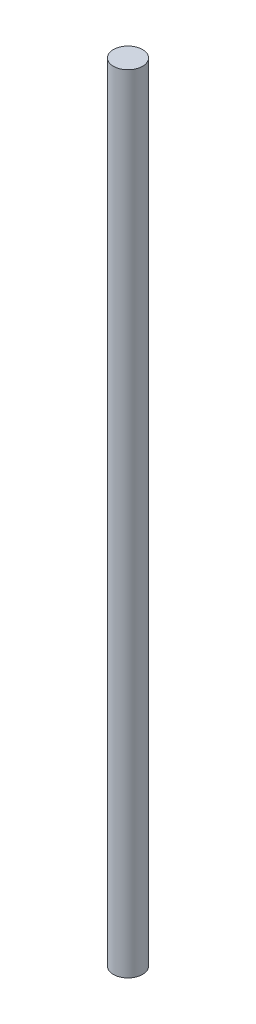
SolidWorks part; units mm, degrees
ref_plane "Front Plane" through (0, 0, 0) normal (0, 0, 1) x (1, 0, 0)
ref_plane "Top Plane" through (0, 0, 0) normal (0, 1, 0) x (1, 0, 0)
ref_plane "Right Plane" through (0, 0, 0) normal (1, 0, 0) x (0, 0, -1)
sketch "Sketch1" plane through (0, 0, 0) normal (0, 1, 0) x (1, 0, 0)
  circle A0 centre (0, 0) radius 1.85
  dimension "D1" = 3.7
extrude "Boss-Extrude1" add sketch "Sketch1" along normal blind 100
